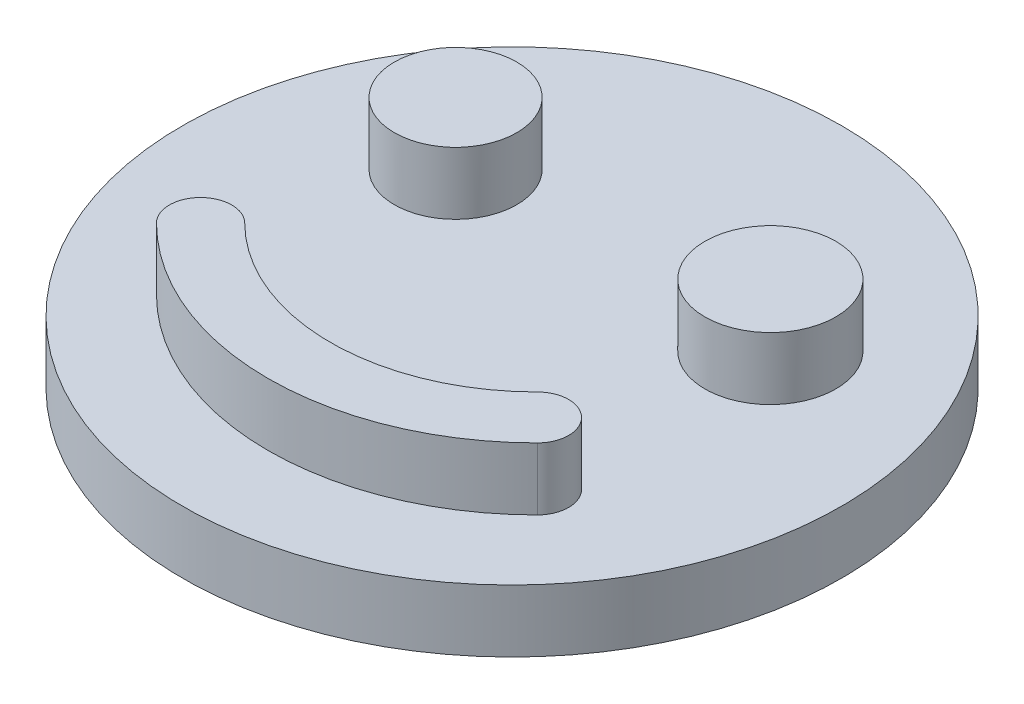
SolidWorks part; units mm, degrees
ref_plane "Front Plane" through (0, 0, 0) normal (0, 0, 1) x (1, 0, 0)
ref_plane "Top Plane" through (0, 0, 0) normal (0, 1, 0) x (1, 0, 0)
ref_plane "Right Plane" through (0, 0, 0) normal (1, 0, 0) x (0, 0, -1)
sketch "Sketch1" plane through (0, 0, 0) normal (0, 1, 0) x (1, 0, 0)
  circle A0 centre (0, 0) radius 54.7671 construction
  circle A1 centre (-31.1199, 20.0592) radius 9.8131
  circle A2 centre (19.3357, 20.0592) radius 10.4983
  arc A3 (-34.1195, -17.8096) -> (19.8718, -17.8096) centre (-7.1238, 9.186) ccw construction
  arc A4 (-37.655, -21.3451) -> (23.4073, -21.3451) centre (-7.1238, 9.186) ccw
  arc A5 (-30.5839, -14.2741) -> (16.3362, -14.2741) centre (-7.1238, 9.186) ccw
  arc A6 (-37.655, -21.3451) -> (-30.5839, -14.2741) centre (-34.1195, -17.8096) cw
  arc A7 (23.4073, -21.3451) -> (16.3362, -14.2741) centre (19.8718, -17.8096) ccw
  arc A8 (-34.1195, -17.8096) -> (19.8718, -17.8096) centre (-7.1238, 9.186) ccw construction
  point P16 (-20.9966, 20.0592)
  point P17 (19.3357, 20.0592)
  point P18 (-31.1199, 20.0592)
  point P19 (0, 0)
  dimension "D1" = 5
  dimension "D2" = 5
extrude "Boss-Extrude1" add sketch "Sketch1" along normal blind 10
sketch "Sketch2" plane through (0, 0, 0) normal (0, -1, 0) x (1, 0, 0)
  circle A0 centre (-6.2511, -4.2469) radius 52.8233
  point P2 (-6.2511, -4.2469)
extrude "Boss-Extrude2" add sketch "Sketch2" along normal blind 10
